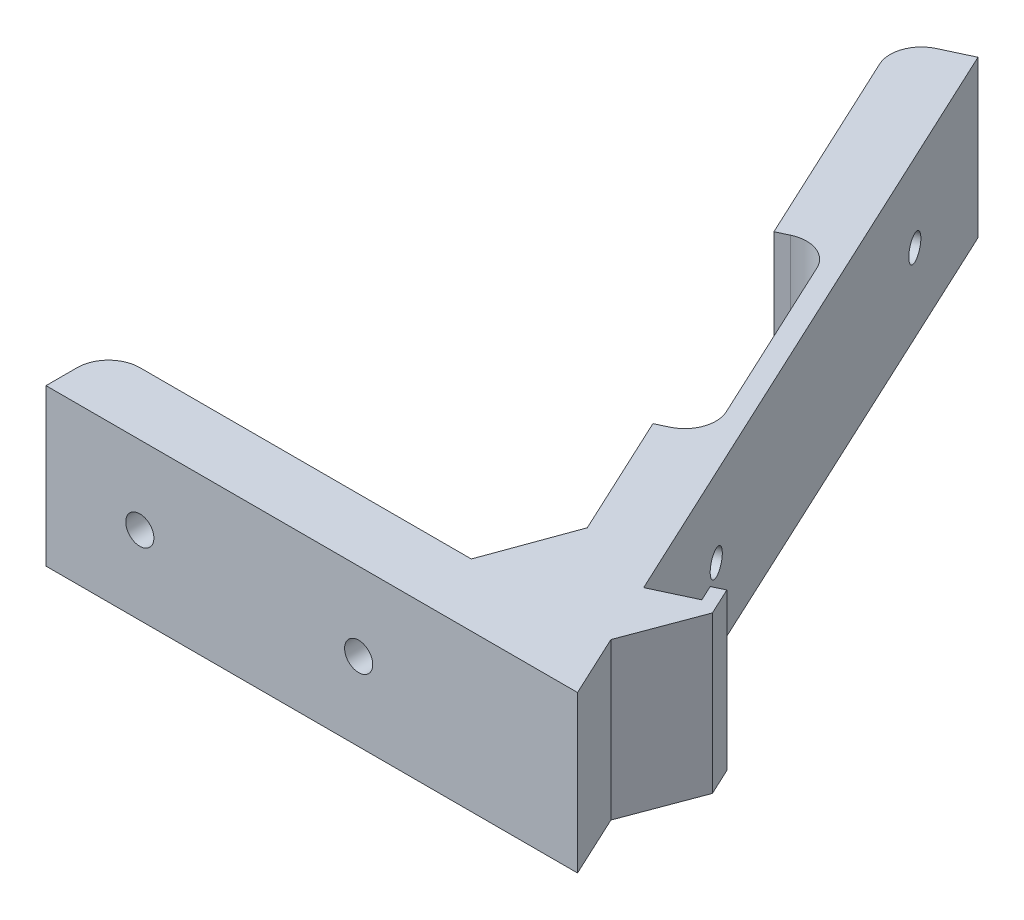
SolidWorks part; units mm, degrees
ref_plane "Front Plane" through (0, 0, 0) normal (0, 0, 1) x (1, 0, 0)
ref_plane "Top Plane" through (0, 0, 0) normal (0, 1, 0) x (1, 0, 0)
ref_plane "Right Plane" through (0, 0, 0) normal (1, 0, 0) x (0, 0, -1)
sketch "Sketch1" plane through (0, 0, 0) normal (0, 1, 0) x (1, 0, 0)
  line L0 (-36.5589, -36.6139) -> (48.4411, -36.6139)
  line L1 (48.4411, -36.6139) -> (-7.5158, 83.3861)
  line L2 (-36.5589, -36.6139) -> (-36.5589, -26.6139)
  line L3 (-36.5589, -26.6139) -> (43.778, -26.6139)
  line L4 (-7.5158, 83.3861) -> (-16.5789, 79.16)
  line L5 (-16.5789, 79.16) -> (37.4073, -36.6139)
  line L6 (26.405, -13.0192) -> (21.4569, -26.6139)
  line L7 (39.2015, -16.7995) -> (47.3583, -12.996)
  line L8 (47.3583, -12.996) -> (48.2035, -14.8086)
  line L9 (48.2035, -14.8086) -> (43.778, -26.6139)
  line L10 (17.2306, 6.6553) -> (0.3258, 42.9076)
  line L11 (17.2306, 6.6553) -> (23.5747, 9.6137)
  line L12 (0.3258, 42.9076) -> (6.67, 45.866)
  line L13 (23.5747, 9.6137) -> (6.67, 45.866)
  line L14 (47.3583, -12.996) -> (45.5457, -13.8412)
  line L15 (47.3583, -12.996) -> (46.1844, -10.4786)
  line L16 (45.5457, -13.8412) -> (44.3718, -11.3238)
  line L17 (46.1844, -10.4786) -> (44.3718, -11.3238)
  point P11 (32.7443, -26.6139)
  dimension "D4" = 10
  dimension "D1" = 85
  dimension "D2" = 65
  dimension "D3" = 120
  dimension "D5" = 10
  dimension "D6" = 135
  dimension "D7" = 2
  dimension "D8" = 15
  dimension "D9" = 3
  dimension "D10" = 40
  dimension "D11" = 2
  dimension "D12" = 9
  dimension "D13" = 40
extrude "Boss-Extrude1" add sketch "Sketch1" along normal blind 25 contours L4 L5 L3 L1 | L5 L3 L2 L0 | L3 L5 L0 L1 | L9 L8 L7 L1 | L5 L6 L3 | L15 L17 L16 L7
fillet "Fillet3" radius 5 1 edges at (-16.5789, 12.5, -79.16)
fillet "Fillet4" radius 5 1 edges at (-36.5589, 12.5, 26.6139)
fillet "Fillet6" radius 5 1 edges at (23.5747, 12.5, -9.6137)
fillet "Fillet7" radius 5 1 edges at (6.67, 12.5, -45.866)
sketch "Sketch3" plane through (25.7653, 0, -12.0146) normal (0.9063, 0, -0.4226) x (-0.4226, 0, -0.9063)
  line L0 (78.7498, 12.5) -> (-31.7928, 12.5) construction
  line L1 (78.7498, 25) -> (78.7498, 0) construction
  line L2 (-31.7928, 25) -> (-31.7928, 0) construction
  circle A0 centre (57.8572, 12.5) radius 2
  circle A1 centre (-7.7928, 12.5) radius 2
  dimension "D1" = 65.65
  dimension "D2" = 24
  dimension "D3" = 4
  dimension "D4" = 4
extrude "Cut-Extrude1" cut sketch "Sketch3" against normal blind 10
sketch "Sketch4" plane through (0, 0, 36.6139) normal (0, 0, 1) x (1, 0, 0)
  line L0 (-36.5589, 12.5) -> (48.4411, 12.5) construction
  line L1 (-36.5589, 25) -> (-36.5589, 0) construction
  line L2 (48.4411, 25) -> (48.4411, 0) construction
  circle A0 centre (-21.5589, 12.5) radius 2.25
  circle A1 centre (13.4411, 12.5) radius 2.25
  dimension "D1" = 4.5
  dimension "D2" = 4.5
  dimension "D3" = 35
  dimension "D4" = 15
extrude "Cut-Extrude2" cut sketch "Sketch4" against normal blind 10
